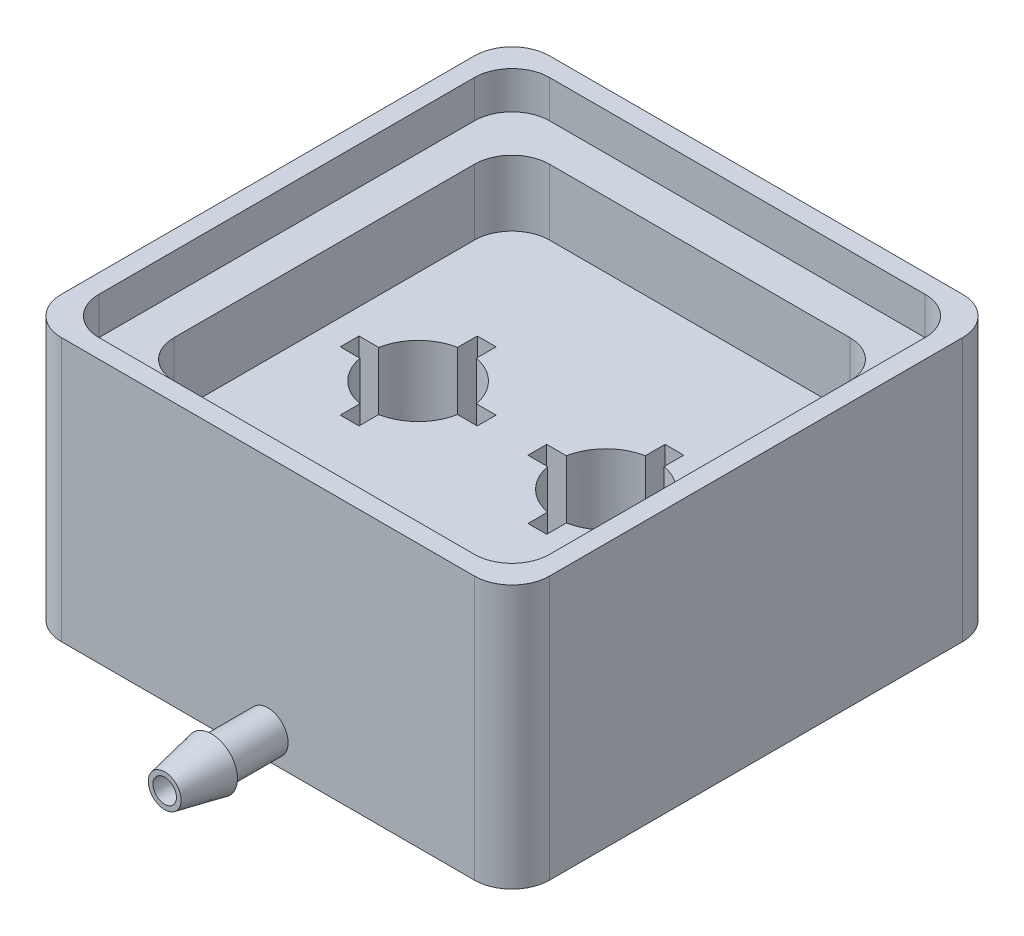
SolidWorks part; units mm, degrees
ref_plane "Front Plane" through (0, 0, 0) normal (0, 0, 1) x (1, 0, 0)
ref_plane "Top Plane" through (0, 0, 0) normal (0, 1, 0) x (1, 0, 0)
ref_plane "Right Plane" through (0, 0, 0) normal (1, 0, 0) x (0, 0, -1)
sketch "Sketch1" plane through (0, 0, 0) normal (0, 1, 0) x (1, 0, 0)
  line L0 (-5, 0) -> (5, 0) construction
  line L1 (-11, -13) -> (11, -13)
  line L2 (-13, -11) -> (-13, 11)
  line L3 (-11, 13) -> (11, 13)
  line L4 (13, -11) -> (13, 11)
  line L5 (-13, -13) -> (13, 13) construction
  line L6 (-13, 13) -> (13, -13) construction
  arc A0 (-13, 11) -> (-11, 13) centre (-11, 11) cw
  arc A1 (11, 13) -> (13, 11) centre (11, 11) cw
  arc A2 (-13, -11) -> (-11, -13) centre (-11, -11) ccw
  arc A3 (13, -11) -> (11, -13) centre (11, -11) cw
  circle A4 centre (5, 0) radius 2.65
  circle A5 centre (-5, 0) radius 2.65
  point P0 (0, 0)
  point P21 (0, 0)
  dimension "D3" = 2
  dimension "D4" = 2
  dimension "D6" = 5.3
  dimension "D7" = 5.3
  dimension "D1" = 26
  dimension "D2" = 26
  dimension "D5" = 10
extrude "Boss-Extrude1" add sketch "Sketch1" along normal blind 8.53
sketch "Sketch2" plane through (0, 8.53, 0) normal (0, 1, 0) x (1, 0, 0)
  line L0 (-5, 0) -> (5, 0) construction
  line L2 (-8.65, -0.5) -> (-1.35, -0.5)
  line L3 (-8.65, -0.5) -> (-8.65, 0.5)
  line L4 (-8.65, 0.5) -> (-1.35, 0.5)
  line L5 (-1.35, -0.5) -> (-1.35, 0.5)
  line L6 (-8.65, -0.5) -> (-1.35, 0.5) construction
  line L7 (-8.65, 0.5) -> (-1.35, -0.5) construction
  line L8 (-5.5, -3.65) -> (-4.5, -3.65)
  line L9 (-5.5, -3.65) -> (-5.5, 3.65)
  line L10 (-5.5, 3.65) -> (-4.5, 3.65)
  line L11 (-4.5, -3.65) -> (-4.5, 3.65)
  line L12 (-5.5, -3.65) -> (-4.5, 3.65) construction
  line L13 (-5.5, 3.65) -> (-4.5, -3.65) construction
  line L14 (4.5, -3.65) -> (5.5, -3.65)
  line L15 (4.5, -3.65) -> (4.5, 3.65)
  line L16 (4.5, 3.65) -> (5.5, 3.65)
  line L17 (5.5, -3.65) -> (5.5, 3.65)
  line L18 (4.5, -3.65) -> (5.5, 3.65) construction
  line L19 (4.5, 3.65) -> (5.5, -3.65) construction
  line L20 (1.35, -0.5) -> (8.65, -0.5)
  line L21 (1.35, -0.5) -> (1.35, 0.5)
  line L22 (1.35, 0.5) -> (8.65, 0.5)
  line L23 (8.65, -0.5) -> (8.65, 0.5)
  line L24 (1.35, -0.5) -> (8.65, 0.5) construction
  line L25 (1.35, 0.5) -> (8.65, -0.5) construction
  point P3 (0, 0)
  circle M15 centre (5, 0) radius 2.65
  circle M16 centre (-5, 0) radius 2.65
  dimension "D1" = 10
  dimension "D2" = 7.3
  dimension "D3" = 7.3
  dimension "D4" = 7.3
  dimension "D5" = 7.3
  dimension "D6" = 1
  dimension "D7" = 1
  dimension "D8" = 1
  dimension "D9" = 1
extrude "Cut-Extrude1" cut sketch "Sketch2" against normal blind 7.785 contours L17 L16 L15 M15 | L20 L23 L22 M15 | L14 L17 L15 M15 | L22 L21 L20 M15 | L2 L5 L4 M16 | L11 L10 L9 M16 | L4 L3 L2 M16 | L8 L11 L9 M16
sketch "Sketch3" plane through (0, 0, 0) normal (1, 0, 0) x (0, 0, -1)
  line L0 (-13, 0.3) -> (-16, 0.3)
  line L1 (-13, 8.53) -> (-13, 0) construction
  line L2 (-16, 0.3) -> (-16, 0)
  line L3 (-16, 0) -> (-18.5, 0.5)
  line L4 (-18.5, 0.5) -> (-18.5, 0.75)
  line L5 (-18.5, 0.75) -> (-13, 0.75)
  line L6 (-13, 0.75) -> (-13, 0.3)
  line L7 (-13, 1.375) -> (-13.6025, 1.375) construction
  line L8 (-11, 0) -> (11, 0) construction
  dimension "D1" = 2.5
  dimension "D2" = 3
  dimension "D3" = 0.875
  dimension "D4" = 1.075
  dimension "D5" = 0.625
  dimension "D6" = 1.375
revolve "Revolve1" add sketch "Sketch3" angle 360 about L7
sketch "Sketch10" plane through (0, 0, 0) normal (1, 0, 0) x (0, 0, -1)
  circle A0 centre (0, 1.375) radius 0.625
extrude "Cut-Extrude3" cut sketch "Sketch10" against normal up to next and the other way up to next
sketch "Sketch5" plane through (0, 0, 13) normal (0, 0, 1) x (1, 0, 0)
  circle A0 centre (0, 1.375) radius 0.625
  dimension "D1" = 1.25
extrude "Cut-Extrude2" cut sketch "Sketch5" against normal up to next
sketch "Sketch6" plane through (0, 8.53, 0) normal (0, 1, 0) x (1, 0, 0)
  line L1 (-11, -13) -> (11, -13)
  line L2 (-13, -11) -> (-13, 11)
  line L3 (-11, 13) -> (11, 13)
  line L4 (13, -11) -> (13, 11)
  line L5 (-13, -13) -> (13, 13) construction
  line L6 (-13, 13) -> (13, -13) construction
  line L7 (-8, -10) -> (8, -10)
  line L8 (-10, -8) -> (-10, 8)
  line L9 (-8, 10) -> (8, 10)
  line L10 (10, -8) -> (10, 8)
  line L11 (-10, -10) -> (10, 10) construction
  line L12 (-10, 10) -> (10, -10) construction
  arc A0 (-13, -11) -> (-11, -13) centre (-11, -11) ccw
  arc A1 (13, -11) -> (11, -13) centre (11, -11) cw
  arc A2 (13, 11) -> (11, 13) centre (11, 11) ccw
  arc A3 (-11, 13) -> (-13, 11) centre (-11, 11) ccw
  arc A4 (-10, -8) -> (-8, -10) centre (-8, -8) ccw
  arc A5 (8, -10) -> (10, -8) centre (8, -8) ccw
  arc A6 (10, 8) -> (8, 10) centre (8, 8) ccw
  arc A7 (-8, 10) -> (-10, 8) centre (-8, 8) ccw
  point P0 (0, 0)
  point P18 (0, 0)
  dimension "D3" = 2
  dimension "D1" = 26
  dimension "D2" = 26
  dimension "D6" = 2
  dimension "D4" = 3
  dimension "D5" = 3
extrude "Boss-Extrude2" add sketch "Sketch6" along normal blind 3.5
sketch "Sketch8" plane through (0, 12.03, 0) normal (0, 1, 0) x (1, 0, 0)
  line L1 (-11, -13) -> (11, -13)
  line L2 (-13, -11) -> (-13, 11)
  line L3 (-11, 13) -> (11, 13)
  line L4 (13, -11) -> (13, 11)
  line L5 (-13, -13) -> (13, 13) construction
  line L6 (-13, 13) -> (13, -13) construction
  line L7 (-10, -12) -> (10, -12)
  line L8 (-12, -10) -> (-12, 10)
  line L9 (-10, 12) -> (10, 12)
  line L10 (12, -10) -> (12, 10)
  line L11 (-12, -12) -> (12, 12) construction
  line L12 (-12, 12) -> (12, -12) construction
  arc A0 (13, 11) -> (11, 13) centre (11, 11) ccw
  arc A1 (13, -11) -> (11, -13) centre (11, -11) cw
  arc A2 (-13, -11) -> (-11, -13) centre (-11, -11) ccw
  arc A3 (-13, 11) -> (-11, 13) centre (-11, 11) cw
  arc A4 (-12, -10) -> (-10, -12) centre (-10, -10) ccw
  arc A5 (10, -12) -> (12, -10) centre (10, -10) ccw
  arc A6 (12, 10) -> (10, 12) centre (10, 10) ccw
  arc A7 (-12, 10) -> (-10, 12) centre (-10, 10) cw
  point P0 (0, 0)
  point P18 (0, 0)
  dimension "D3" = 2
  dimension "D1" = 26
  dimension "D2" = 26
  dimension "D6" = 2
  dimension "D4" = 1
  dimension "D5" = 1
extrude "Boss-Extrude3" add sketch "Sketch8" along normal blind 2
equation "\"D2@Sketch1\"=\"D1@Sketch1\""
equation "\"D7@Sketch1\"=\"D6@Sketch1\""
equation "\"D3@Sketch2\"=\"D2@Sketch2\""
equation "\"D2@Sketch2\"=\"D6@Sketch1\"+2mm"
equation "\"D4@Sketch2\"=\"D2@Sketch2\""
equation "\"D5@Sketch2\"=\"D2@Sketch2\""
equation "\"D7@Sketch2\"=\"D6@Sketch2\""
equation "\"D8@Sketch2\"=\"D6@Sketch2\""
equation "\"D9@Sketch2\"=\"D6@Sketch2\""
equation "\"D1@Sketch6\"=\"D1@Sketch1\""
equation "\"D2@Sketch6\"=\"D1@Sketch1\""
equation "\"D5@Sketch6\"=\"D4@Sketch6\""
equation "\"D1@Sketch8\"=\"D1@Sketch1\""
equation "\"D2@Sketch8\"=\"D1@Sketch1\""
equation "\"D1@Sketch2\"=\"D5@Sketch1\""
